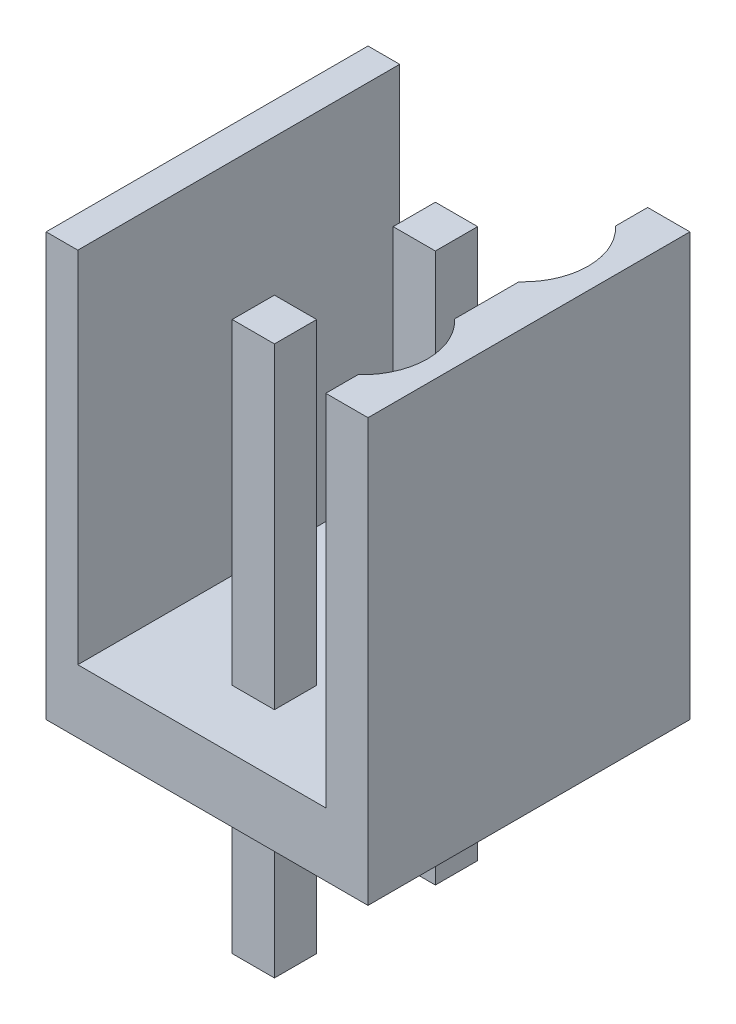
SolidWorks part; units mm, degrees
ref_plane "前视基准面" through (0, 0, 0) normal (0, 0, 1) x (1, 0, 0)
ref_plane "上视基准面" through (0, 0, 0) normal (0, 1, 0) x (1, 0, 0)
ref_plane "右视基准面" through (0, 0, 0) normal (1, 0, 0) x (0, 0, -1)
sketch "草图1" plane through (0, 0, 0) normal (0, 1, 0) x (1, 0, 0)
  line L0 (0, 11.3571) -> (0, -8.6742) construction
  line L1 (-3.81, 3.81) -> (3.81, 3.81)
  line L2 (-3.81, 3.81) -> (-3.81, -3.81)
  line L3 (-3.81, -3.81) -> (3.81, -3.81)
  line L4 (3.81, 3.81) -> (3.81, -3.81)
  line L5 (-11.8577, 0) -> (16.1453, 0) construction
  dimension "D1" = 7.62
  dimension "D2" = 7.62
extrude "拉伸1" add sketch "草图1" along normal blind 10
sketch "草图2" plane through (0, 10, 0) normal (0, 1, 0) x (-1, 0, 0)
  line L0 (-4.9146, 0) -> (4.5942, 0) construction
  line L1 (-1.7494, -1.905) -> (-4.2075, -1.905) construction
  line L2 (-2.81, -3.81) -> (-2.81, -3.0498)
  line L3 (-3.81, -3.81) -> (3.81, -3.81) construction
  line L4 (-3.81, 3.81) -> (-3.81, -3.81) construction
  line L5 (-3.31, -1.905) -> (-3.31, -3.9781) construction
  line L6 (-2.81, -3.81) -> (3.06, -3.81)
  line L7 (3.06, -3.81) -> (3.06, 3.81)
  line L8 (-2.81, -0.7602) -> (-2.81, 0.7602)
  line L9 (3.81, -3.81) -> (3.81, 3.81) construction
  line L10 (-2.81, 3.81) -> (3.06, 3.81)
  line L11 (-2.81, 3.81) -> (-2.81, 3.0498)
  arc A0 (-2.81, 0.7602) -> (-2.81, 3.0498) centre (-1.7494, 1.905) cw
  arc A1 (-2.81, -0.7602) -> (-2.81, -3.0498) centre (-1.7494, -1.905) ccw
  point P16 (-2.81, 0)
  point P25 (3.06, 0)
  dimension "D1" = 1.905
  dimension "D2" = 1.5606
  dimension "D4" = 0.5
  dimension "D3" = 1
  dimension "D5" = 0.75
extrude "切除-拉伸1" cut sketch "草图2" against normal offset from surface (8.5 mm away) 1.5 up to face at (0, 0, 0)
sketch "草图3" plane through (0, 0, 0) normal (0, -1, 0) x (1, 0, 0)
  line L0 (4.5117, 0) -> (-4.6667, 0) construction
  line L1 (2.1187, 1.905) -> (-2.5308, 1.905) construction
  line L2 (0.19, 2.405) -> (-0.81, 2.405)
  line L3 (0.19, 2.405) -> (0.19, 1.405)
  line L4 (0.19, 1.405) -> (-0.81, 1.405)
  line L5 (-0.81, 2.405) -> (-0.81, 1.405)
  line L6 (-0.31, 3.5474) -> (-0.31, 0.8266) construction
  line L7 (-3.81, -3.81) -> (-3.81, 3.81) construction
  line L8 (-0.81, -2.405) -> (-0.81, -1.405)
  line L9 (0.19, -1.405) -> (-0.81, -1.405)
  line L10 (0.19, -2.405) -> (0.19, -1.405)
  line L11 (0.19, -2.405) -> (-0.81, -2.405)
  dimension "D1" = 1
  dimension "D2" = 1
  dimension "D3" = 1.905
  dimension "D4" = 3.5
extrude "拉伸2" add sketch "草图3" along normal blind 4 and the other way offset from surface (9 mm away) 1 other way up to face at (-3.435, 10, 0)
